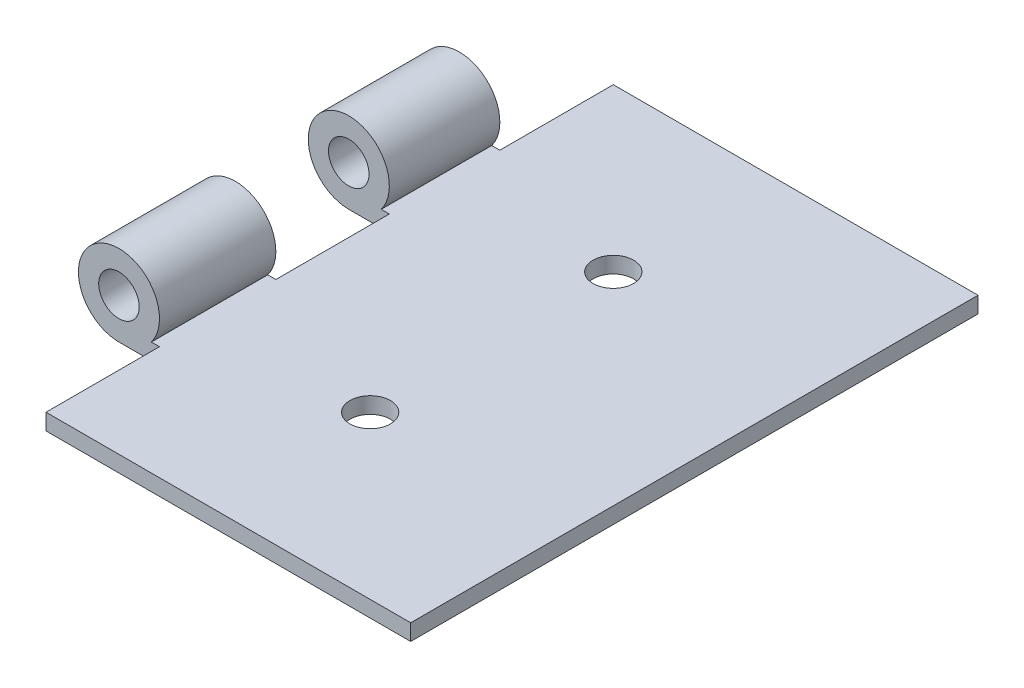
SolidWorks part; units mm, degrees
ref_plane "Front Plane" through (0, 0, 0) normal (0, 0, 1) x (1, 0, 0)
ref_plane "Top Plane" through (0, 0, 0) normal (0, 1, 0) x (1, 0, 0)
ref_plane "Right Plane" through (0, 0, 0) normal (1, 0, 0) x (0, 0, -1)
sketch "Sketch1" plane through (0, 0, 0) normal (0, 1, 0) x (1, 0, 0)
  line L1 (-25, 35) -> (25, 35)
  line L2 (-25, 35) -> (-25, -35)
  line L3 (-25, -35) -> (25, -35)
  line L4 (25, 35) -> (25, -35)
  line L5 (-25, 35) -> (25, -35) construction
  line L6 (-25, -35) -> (25, 35) construction
  point P0 (0, 0)
  dimension "D1" = 70
  dimension "D2" = 50
extrude "Boss-Extrude1" add sketch "Sketch1" along normal blind 2
sketch "Sketch2" plane through (0, 0, 35) normal (0, 0, 1) x (1, 0, 0)
  circle A0 centre (-25, 5) radius 2.5
  circle A1 centre (-25, 5) radius 5
  dimension "D1" = 10
  dimension "D2" = 5
extrude "Boss-Extrude2" add sketch "Sketch2" against normal up to surface (70 mm away) up to face at (0, 1, -35)
sketch "Sketch3" plane through (0, 2, 0) normal (0, 1, 0) x (1, 0, 0)
  line L0 (25, -35) -> (25, 35) construction
  line L1 (-21, -35) -> (25, -35) construction
  line L2 (25, 35) -> (-21, 35) construction
  circle A0 centre (0, 15) radius 2.5
  circle A1 centre (0, -15) radius 2.5
  dimension "D1" = 5
  dimension "D2" = 5
  dimension "D4" = 25
  dimension "D5" = 20
  dimension "D6" = 20
  dimension "D3" = 25
extrude "Cut-Extrude1" cut sketch "Sketch3" against normal through all
sketch "Sketch4" plane through (0, 2, 0) normal (0, 1, 0) x (1, 0, 0)
  line L0 (-20, -35) -> (-20, 35) construction
  line L1 (-30, 35) -> (-20, 35)
  line L2 (-30, 35) -> (-30, 21)
  line L3 (-30, 21) -> (-20, 21)
  line L4 (-20, 35) -> (-20, 21)
  line L5 (-30, 35) -> (-30, -35) construction
  line L6 (-30, 7.3604) -> (-20, 7.3604)
  line L7 (-30, 7.3604) -> (-30, -6.6396)
  line L8 (-30, -6.6396) -> (-20, -6.6396)
  line L9 (-20, 7.3604) -> (-20, -6.6396)
  line L11 (-30, -35) -> (-20, -35)
  line L12 (-30, -35) -> (-30, -21)
  line L13 (-30, -21) -> (-20, -21)
  line L14 (-20, -35) -> (-20, -21)
  point P18 (-25, -21)
  dimension "D1" = 14
  dimension "D2" = 14
  dimension "D3" = 14
  dimension "D4" = 14.3604
extrude "Cut-Extrude2" cut sketch "Sketch4" against normal through all both and the other way through all
